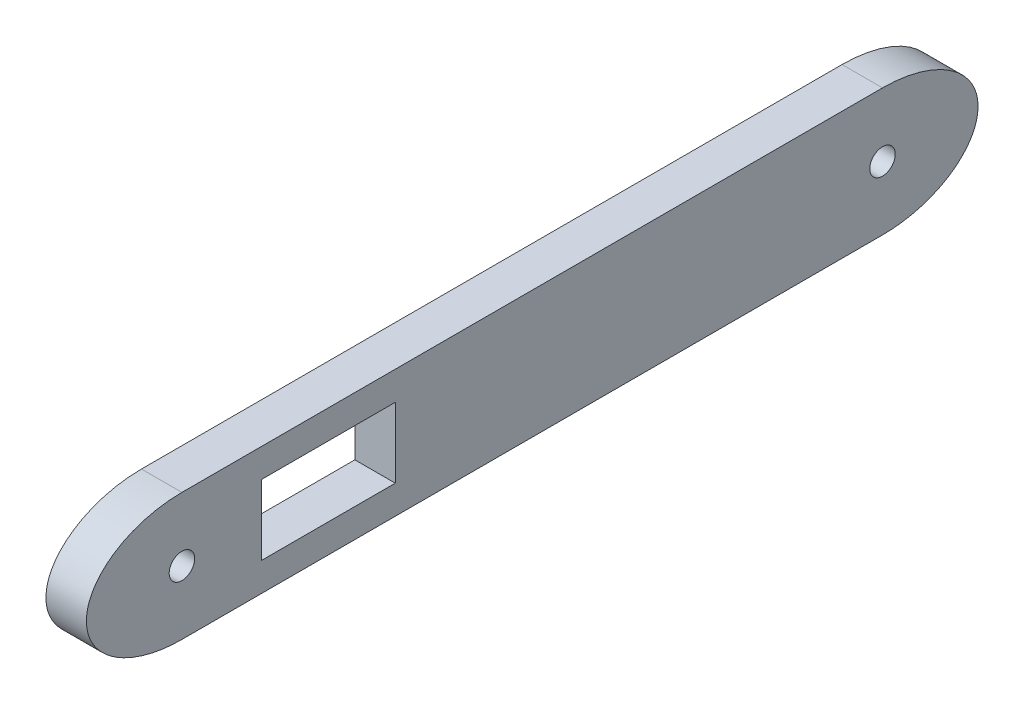
SolidWorks part; units mm, degrees
ref_plane "Front Plane" through (0, 0, 0) normal (0, 0, 1) x (1, 0, 0)
ref_plane "Top Plane" through (0, 0, 0) normal (0, 1, 0) x (1, 0, 0)
ref_plane "Right Plane" through (0, 0, 0) normal (1, 0, 0) x (0, 0, -1)
sketch "Sketch1" plane through (0, 0, 0) normal (1, 0, 0) x (0, 0, -1)
  line L0 (0, 55) -> (0, -55) construction
  line L5 (-110, -20) -> (110, -20)
  line L6 (-110, -20) -> (-110, 20)
  line L7 (-110, 20) -> (110, 20)
  line L8 (110, -20) -> (110, 20)
  line L9 (-110, -20) -> (110, 20) construction
  line L10 (-110, 20) -> (110, -20) construction
  ellipse E0 centre (-110, 0) end of major axis (-80, 0) minor radius 20
  ellipse E1 centre (110, 0) end of major axis (80, 0) minor radius 20
  point P0 (0, 0)
  point P1 (0, 0)
  point P21 (0, 0)
  point P22 (0, 0)
  point P23 (0, 0)
  dimension "D1" = 220
  dimension "D2" = 40
  dimension "D3" = 30
extrude "Boss-Extrude1" add sketch "Sketch1" along normal blind 12.7 contours L5 E1 L7 E0 | E1 L8 | E1 L8
sketch "Sketch2" plane through (12.7, 0, 0) normal (1, 0, 0) x (0, 0, -1)
  line L1 (0, 55) -> (0, -55) construction
  line L2 (-110, 20) -> (110, 20) construction
  line L3 (-85, 11) -> (-43, 11)
  line L4 (-85, 11) -> (-85, -11)
  line L5 (-85, -11) -> (-43, -11)
  line L6 (-43, 11) -> (-43, -11)
  line L7 (-85, 11) -> (-43, -11) construction
  line L8 (-85, -11) -> (-43, 11) construction
  circle A0 centre (-110, 0) radius 4
  circle A1 centre (110, 0) radius 4
  ellipse E0 centre (-110, 0) end of major axis (-140, 0) minor radius 20 (-110, 20) -> (-110, -20) ccw construction
  point P13 (-64, 0)
  dimension "D1" = 8
  dimension "D2" = 42
  dimension "D3" = 22
  dimension "D4" = 25
  dimension "D5" = 9
extrude "Cut-Extrude1" cut sketch "Sketch2" against normal blind 12.7
